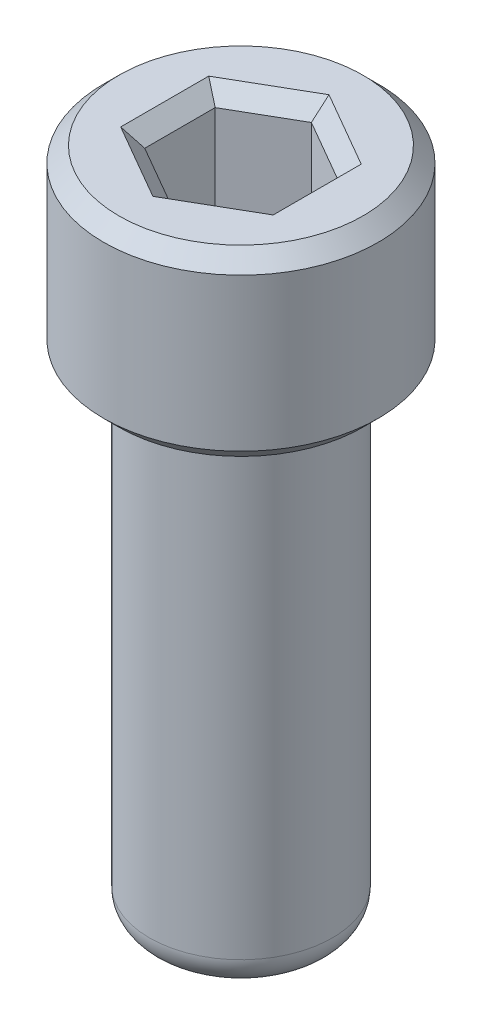
SolidWorks part; units mm, degrees
ref_plane "Front Plane" through (0, 0, 0) normal (0, 0, 1) x (1, 0, 0)
ref_plane "Top Plane" through (0, 0, 0) normal (0, 1, 0) x (1, 0, 0)
ref_plane "Right Plane" through (0, 0, 0) normal (1, 0, 0) x (0, 0, -1)
sketch "Sketch1" plane through (0, 0, 0) normal (0, 1, 0) x (1, 0, 0)
  circle A0 centre (0, 0) radius 1.5
  dimension "D1" = 3
extrude "Boss-Extrude1" add sketch "Sketch1" along normal blind 8
sketch "Sketch2" plane through (0, 8, 0) normal (0, 1, 0) x (1, 0, 0)
  circle A0 centre (0, 0) radius 2.25
  dimension "D1" = 4.5
extrude "Boss-Extrude2" add sketch "Sketch2" along normal blind 3
sketch "Sketch3" plane through (0, 11, 0) normal (0, 1, 0) x (1, 0, 0)
  line L1 (0, 1.1547) -> (-1, 0.5774)
  line L2 (-1, 0.5774) -> (-1, -0.5774)
  line L3 (-1, -0.5774) -> (0, -1.1547)
  line L4 (0, -1.1547) -> (1, -0.5774)
  line L5 (1, -0.5774) -> (1, 0.5774)
  line L6 (1, 0.5774) -> (0, 1.1547)
  circle A0 centre (0, 0) radius 1 construction
extrude "Cut-Extrude1" cut sketch "Sketch3" against normal blind 2
chamfer "Chamfer1" distance 0.25 angle 45 8 edges at (0, 8, 2.25) (0, 11, 2.25) (-0.5, 11, 0.866) (-1, 11, 0) (-0.5, 11, -0.866) (0.5, 11, -0.866) (1, 11, 0) (0.5, 11, 0.866)
fillet "Fillet1" radius 0.5 1 edges at (0, 0, 1.5)
